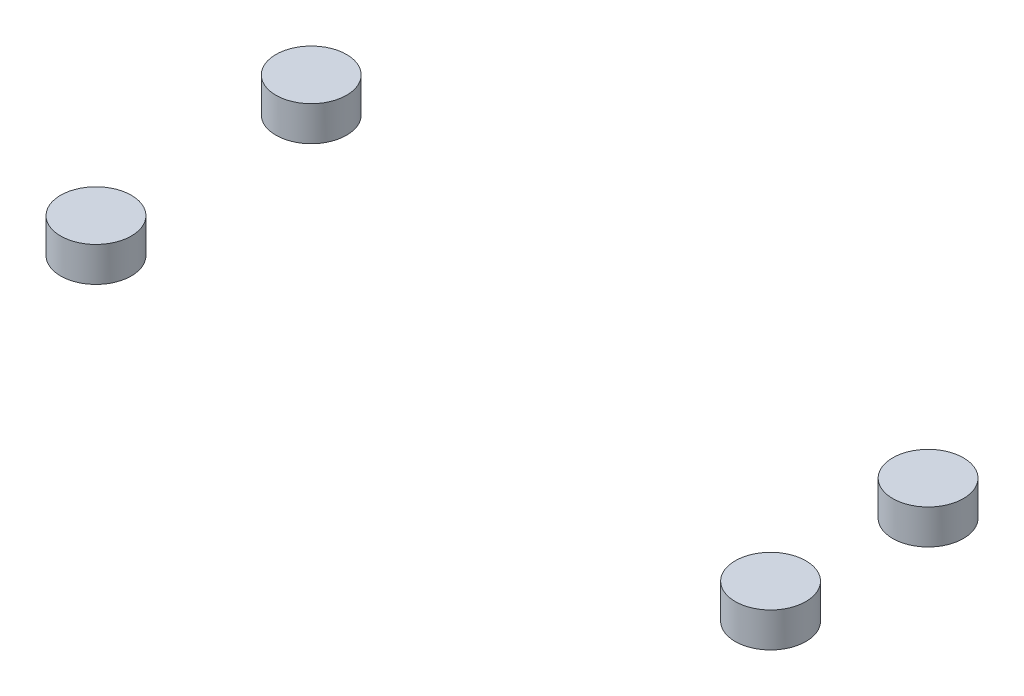
SolidWorks part; units mm, degrees
ref_plane "Front Plane" through (0, 0, 0) normal (0, 0, 1) x (1, 0, 0)
ref_plane "Top Plane" through (0, 0, 0) normal (0, 1, 0) x (1, 0, 0)
ref_plane "Right Plane" through (0, 0, 0) normal (1, 0, 0) x (0, 0, -1)
sketch "Sketch3" plane through (0, 0, 0) normal (0, 1, 0) x (1, 0, 0)
  circle A4 centre (70.365, 22.068) radius 8.001
  circle A5 centre (72.7273, -15.9595) radius 8.001
  circle A6 centre (-78.5517, 31.3189) radius 8.001
  circle A7 centre (-75.3231, -20.6521) radius 8.001
extrude "Boss-Extrude1" add sketch "Sketch3" along normal up to surface (7.8486 mm away)
